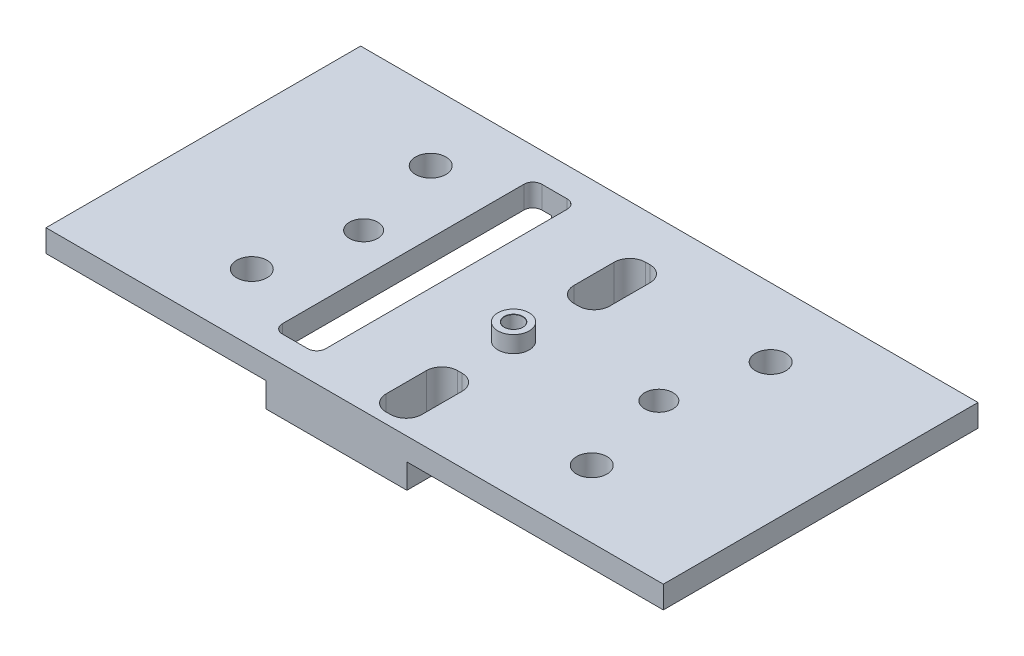
SolidWorks part; units mm, degrees
material "6061 Alloy"
ref_plane "Front Plane" through (0, 0, 0) normal (0, 0, 1) x (1, 0, 0)
ref_plane "Top Plane" through (0, 0, 0) normal (0, 1, 0) x (1, 0, 0)
ref_plane "Right Plane" through (0, 0, 0) normal (1, 0, 0) x (0, 0, -1)
sketch "Sketch1" plane through (0, 0, 0) normal (0, 1, 0) x (1, 0, 0)
  line L1 (0, 0) -> (60, 0)
  line L2 (0, 0) -> (0, 35.17)
  line L3 (0, 35.17) -> (60, 35.17)
  line L4 (60, 0) -> (60, 35.17)
  dimension "D1" = 60
  dimension "D2" = 35.17
extrude "Boss-Extrude1" add sketch "Sketch1" along normal blind 2.5
sketch "Sketch2" plane through (0, 0, 0) normal (0, 0, 1) x (1, 0, 0)
  line L0 (0, 0) -> (60, 0) construction
  line L1 (38.25, 0) -> (22, 0)
  line L2 (38.25, 0) -> (38.25, -2.75)
  line L3 (38.25, -2.75) -> (22, -2.75)
  line L4 (22, 0) -> (22, -2.75)
  line L7 (0, 2.5) -> (0, 0) construction
  dimension "D1" = 2.75
  dimension "D2" = 16.25
  dimension "D3" = 22
extrude "Boss-Extrude2" add sketch "Sketch2" against normal through all
sketch "Sketch3" plane through (0, -2.75, 0) normal (0, -1, 0) x (1, 0, 0)
  line L10 (21.16, -31.92) -> (24, -31.92)
  line L11 (25, -30.92) -> (25, -3.92)
  line L12 (24, -2.92) -> (21.16, -2.92)
  line L13 (20.16, -3.92) -> (20.16, -30.92)
  arc A6 (20.16, -30.92) -> (21.16, -31.92) centre (21.16, -30.92) ccw
  arc A7 (24, -31.92) -> (25, -30.92) centre (24, -30.92) ccw
  arc A8 (25, -3.92) -> (24, -2.92) centre (24, -3.92) ccw
  arc A9 (21.16, -2.92) -> (20.16, -3.92) centre (21.16, -3.92) ccw
  dimension "D2" = 1
  dimension "D3" = 1
  dimension "D4" = 1
  dimension "D5" = 1
  dimension "D1" = 27
  dimension "D6" = 4.84
extrude "Cut-Extrude1" cut sketch "Sketch3" against normal through all
sketch "Sketch4" plane through (0, 2.5, 0) normal (0, 1, 0) x (1, 0, 0)
  line L0 (32.7475, 2.92) -> (32.7475, 7.42)
  line L2 (36.7475, 7.42) -> (36.7475, 2.92)
  line L4 (34.4975, 1.17) -> (34.9975, 1.17)
  line L9 (34.7475, 17.0603) -> (34.7475, 8.5661) construction
  line L10 (32.7475, 5.17) -> (36.7475, 5.17) construction
  line L11 (34.4975, 9.17) -> (34.9975, 9.17)
  line L12 (0, 0) -> (60, 0) construction
  line L13 (32.7475, 28.42) -> (32.7475, 23.92)
  line L15 (34.4975, 22.17) -> (34.9975, 22.17)
  line L16 (25, 30.92) -> (25, 3.92) construction
  line L18 (36.7475, 23.92) -> (36.7475, 28.42)
  line L20 (34.9975, 30.17) -> (34.4975, 30.17)
  line L22 (60, 35.17) -> (0, 35.17) construction
  arc A0 (32.7475, 2.92) -> (34.4975, 1.17) centre (34.4975, 2.92) ccw
  arc A1 (36.7475, 2.92) -> (34.9975, 1.17) centre (34.9975, 2.92) cw
  arc A2 (32.7475, 7.42) -> (34.4975, 9.17) centre (34.4975, 7.42) cw
  arc A3 (36.7475, 7.42) -> (34.9975, 9.17) centre (34.9975, 7.42) ccw
  arc A6 (32.7475, 28.42) -> (34.4975, 30.17) centre (34.4975, 28.42) cw
  arc A7 (34.9975, 30.17) -> (36.7475, 28.42) centre (34.9975, 28.42) cw
  arc A8 (36.7475, 23.92) -> (34.9975, 22.17) centre (34.9975, 23.92) cw
  arc A9 (34.4975, 22.17) -> (32.7475, 23.92) centre (34.4975, 23.92) cw
  point P10 (34.7475, 1.17)
  dimension "D4" = 0.5
  dimension "D3" = 1.75
  dimension "D11" = 1.75
  dimension "D12" = 1.75
  dimension "D13" = 1.75
  dimension "D14" = 1.75
  dimension "D1" = 4.5
  dimension "D2" = 4
  dimension "D5" = 1.17
  dimension "D6" = 4.5
  dimension "D7" = 4
  dimension "D8" = 0.5
  dimension "D9" = 4.5
  dimension "D10" = 0.5
  dimension "D15" = 5
  dimension "D16" = 7.7475
  dimension "D17" = 7.7475
extrude "Cut-Extrude2" cut sketch "Sketch4" against normal through all
sketch "Sketch5" plane through (0, 2.5, 0) normal (0, 1, 0) x (1, 0, 0)
  line L0 (36.7475, 2.92) -> (36.7475, 7.42) construction
  line L1 (60, 0) -> (60, 35.17) construction
  circle A0 centre (34.7475, 15.17) radius 1.75
  point P4 (36.7475, 5.17)
  dimension "D1" = 3.5
  dimension "D2" = 10
  dimension "D3" = 25.2525
extrude "Boss-Extrude3" add sketch "Sketch5" along normal blind 1.85
sketch "Sketch6" plane through (0, 4.35, 0) normal (0, 1, 0) x (1, 0, 0)
  point P0 (34.7475, 15.17)
hole_wizard "Tap Drill for M2.5x0.45 Tap1" positions "Sketch7" profile "Sketch8" hole size "M2.5x0.45" standard "ANSI Metric"
sketch "Sketch7" plane through (0, 4.35, 0) normal (0, 1, 0) x (1, 0, 0)
  point P0 (34.7475, 15.17)
sketch "Sketch8" plane through (34.7475, 4.35, -15.17) normal (1, 0, 0) x (0, 0, 1)
  line L0 (0, 0) -> (0, 4.6159)
  line L1 (0, 4.6159) -> (1.025, 4)
  line L2 (1.025, 4) -> (1.025, 0.025)
  line L3 (1.025, 0.025) -> (1.05, 0)
  line L5 (1.05, 0) -> (0, 0)
  line L6 (-1.025, 0.025) -> (-1.05, 0) construction
  line L10 (0, 4.6159) -> (-1.025, 4) construction
  line L11 (0, -6.35) -> (0, 107.95) construction
  dimension "Hole Dia." = 2.05
  dimension "Hole Depth" = 4
  dimension "Near C'Sink Dia." = 2.1
  dimension "Near C'Sink Angle" = 90
  dimension "Drill Angle" = 118
sketch "Sketch14" plane through (0, -2.75, 0) normal (0, -1, 0) x (1, 0, 0)
  line L0 (22, -35.17) -> (38.25, -35.17) construction
  line L1 (38.25, -35.17) -> (38.25, 0) construction
  circle A0 centre (28.5, -25.31) radius 2.85
  circle A1 centre (34.5, -18.31) radius 2.85
  circle A2 centre (31, -11.31) radius 2.85
  circle A3 centre (29, -4.31) radius 2.85
  circle A4 centre (32.18, -32.31) radius 2.35
  dimension "D1" = 5.7
  dimension "D2" = 5.7
  dimension "D3" = 5.7
  dimension "D4" = 5.7
  dimension "D5" = 4.7
  dimension "D6" = 2.86
  dimension "D7" = 6.07
  dimension "D8" = 7
  dimension "D9" = 7
  dimension "D10" = 7
  dimension "D11" = 7
  dimension "D12" = 2
  dimension "D13" = 3.5
  dimension "D14" = 6
  dimension "D15" = 3.68
extrude "Cut-Extrude4" cut sketch "Sketch14" against normal blind 0.5
sketch "Sketch15" plane through (0, 0, -35.17) normal (0, 0, -1) x (-1, 0, 0)
  line L0 (-60, 2.5) -> (0, 2.5) construction
  line L1 (0, 0) -> (-4.66, 0)
  line L2 (0, 0) -> (0, 2.5)
  line L3 (0, 2.5) -> (-4.66, 2.5)
  line L4 (-4.66, 0) -> (-4.66, 2.5)
  line L6 (-60, 0) -> (-59.66, 0)
  line L7 (-60, 0) -> (-60, 2.5)
  line L8 (-60, 2.5) -> (-59.66, 2.5)
  line L9 (-59.66, 0) -> (-59.66, 2.5)
  dimension "D1" = 0.34
  dimension "D2" = 4.66
extrude "Cut-Extrude5" cut sketch "Sketch15" against normal through all
sketch "Sketch9" plane through (0, 2.5, 0) normal (0, 1, 0) x (1, 0, 0)
  line L1 (4.66, 0) -> (4.66, 35.17) construction
  line L4 (4.66, 0) -> (59.66, 0) construction
  line L5 (59.66, 0) -> (59.66, 35.17) construction
  line L6 (4.66, 0) -> (59.66, 0) construction
  circle A0 centre (15.66, 17.5) radius 1.58
  circle A1 centre (48.66, 17.5) radius 1.58
  dimension "D1" = 3.16
  dimension "D2" = 3.16
  dimension "D3" = 11
  dimension "D4" = 11
  dimension "D5" = 17.5
  dimension "D6" = 17.5
extrude "Cut-Extrude3" cut sketch "Sketch9" against normal through all
sketch "Sketch11" plane through (0, 2.5, 0) normal (0, 1, 0) x (1, 0, 0)
  line L1 (59.66, 0) -> (59.66, 35.17) construction
  line L2 (4.66, 0) -> (4.66, 35.17) construction
  circle A0 centre (13.16, 27.5) radius 1
  circle A1 centre (13.16, 7.5) radius 1
  circle A2 centre (51.16, 27.5) radius 1
  circle A3 centre (51.16, 7.5) radius 1
  circle A4 centre (48.66, 17.5) radius 1.58 construction
  circle A5 centre (15.66, 17.5) radius 1.58 construction
  dimension "D1" = 2
  dimension "D2" = 2
  dimension "D3" = 2
  dimension "D4" = 2
  dimension "D5" = 20
  dimension "D6" = 10
  dimension "D7" = 8.5
  dimension "D8" = 8.5
  dimension "D9" = 20
  dimension "D10" = 10
  dimension "D11" = 8.5
  dimension "D12" = 8.5
hole_wizard "M3 Clearance Hole1" positions "Sketch12" profile "Sketch13" hole size "M3" standard "ANSI Metric" end condition through all
sketch "Sketch12" plane through (0, 2.5, 0) normal (0, 1, 0) x (1, 0, 0)
  point P0 (13.16, 7.5)
  point P3 (13.16, 27.5)
  point P6 (51.16, 27.5)
  point P9 (51.16, 7.5)
sketch "Sketch13" plane through (13.16, 2.5, -7.5) normal (1, 0, 0) x (0, 0, 1)
  line L0 (0, 0) -> (0, 5.25)
  line L1 (0, 5.25) -> (1.7, 5.25)
  line L2 (1.7, 5.25) -> (1.7, 0)
  line L5 (1.7, 0) -> (0, 0)
  line L11 (0, -6.35) -> (0, 107.95) construction
  dimension "Thru Hole Dia." = 3.4
  dimension "Thru Hole Depth" = 5.25
sketch "Sketch17" plane through (0, 0, 0) normal (0, 0, 1) x (1, 0, 0)
  line L0 (4.66, 0) -> (22, 0) construction
  line L1 (59.66, 0) -> (66.66, 0)
  line L2 (59.66, 0) -> (59.66, 2.5)
  line L3 (59.66, 2.5) -> (66.66, 2.5)
  line L4 (66.66, 0) -> (66.66, 2.5)
  line L5 (4.66, 0) -> (-2.34, 0)
  line L6 (4.66, 0) -> (4.66, 2.5)
  line L7 (4.66, 2.5) -> (-2.34, 2.5)
  line L8 (-2.34, 0) -> (-2.34, 2.5)
  line L9 (4.66, 2.5) -> (4.66, 0) construction
  dimension "D1" = 7
  dimension "D2" = 0
  dimension "D3" = 2.5
  dimension "D4" = 7
  dimension "D5" = 2.5
extrude "Boss-Extrude4" add sketch "Sketch17" against normal up to surface (35.17 mm away) up to face at (31.1425, -0.0625, -35.17)
sketch "Sketch18" plane through (0, 0, 0) normal (0, 0, 1) x (1, 0, 0)
  line L0 (22, -2.75) -> (38.25, -2.75) construction
  line L1 (38.25, 0) -> (38, 0)
  line L2 (38.25, 0) -> (38.25, -2.75)
  line L3 (38.25, -2.75) -> (38, -2.75)
  line L4 (38, 0) -> (38, -2.75)
  line L6 (22, 0) -> (22.25, 0)
  line L7 (22, 0) -> (22, -2.75)
  line L8 (22, -2.75) -> (22.25, -2.75)
  line L9 (22.25, 0) -> (22.25, -2.75)
  dimension "D1" = 0.25
  dimension "D2" = 0.25
extrude "Cut-Extrude6" cut sketch "Sketch18" against normal through all
